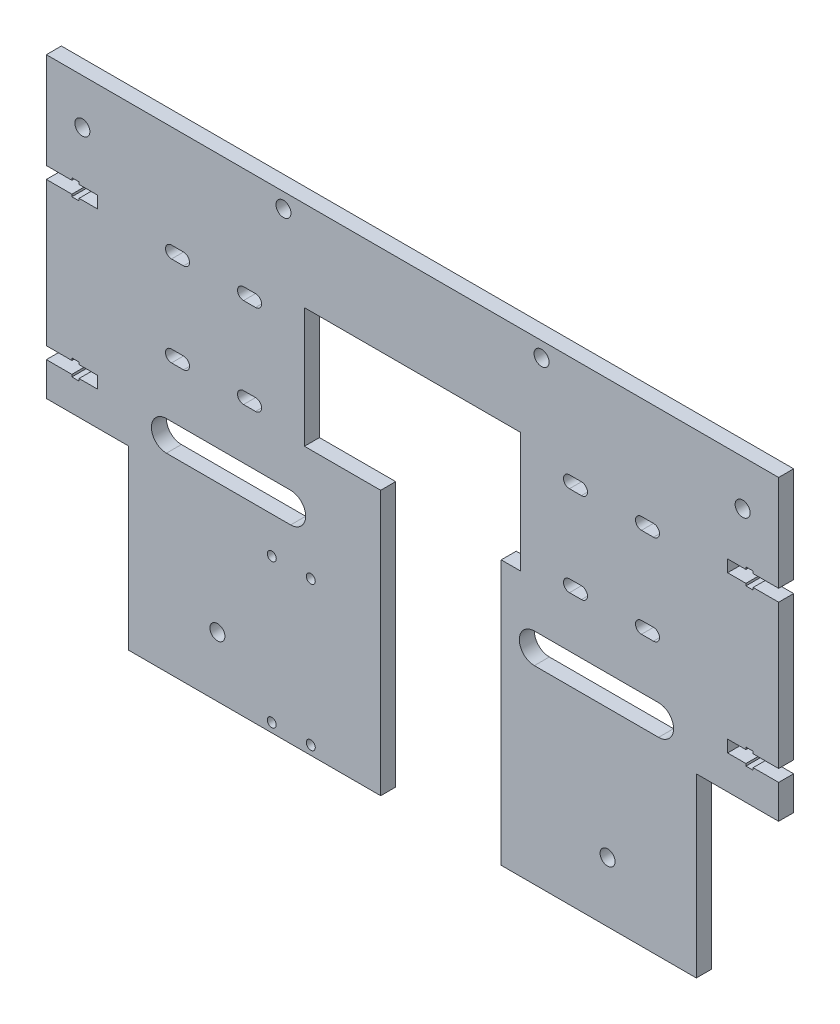
SolidWorks part; units mm, degrees
ref_plane "Front Plane" through (0, 0, 0) normal (0, 0, 1) x (1, 0, 0)
ref_plane "Top Plane" through (0, 0, 0) normal (0, 1, 0) x (1, 0, 0)
ref_plane "Right Plane" through (0, 0, 0) normal (1, 0, 0) x (0, 0, -1)
sketch "Sketch1" plane through (0, 0, 0) normal (0, 0, 1) x (1, 0, 0)
  line L12 (-36.308, -115.936) -> (-36.308, 42.2186)
  line L16 (-36.308, -115.936) -> (-280.308, -115.936)
  line L18 (-280.308, -115.936) -> (-280.308, 42.2186)
  line L20 (-280.308, 42.2186) -> (-36.308, 42.2186)
  dimension "D1" = 244
  dimension "D2" = 158.1546
extrude "Boss-Extrude1" add sketch "Sketch1" along normal blind 5
sketch "Sketch7" plane through (0, 0, 0) normal (0, 0, -1) x (-1, 0, 0)
  line L6 (280.308, -57.0152) -> (252.8877, -57.0152)
  line L7 (252.8877, -57.0152) -> (252.8877, -115.936)
  line L8 (280.308, -115.936) -> (36.308, -115.936) construction
  line L10 (280.308, -115.936) -> (280.308, -57.0152)
  line L11 (280.308, -115.936) -> (252.8877, -115.936)
  line L12 (158.308, -115.936) -> (158.308, 20.5632) construction
  line L13 (36.308, -115.936) -> (63.7283, -115.936)
  line L14 (63.7283, -57.0152) -> (63.7283, -115.936)
  line L15 (36.308, -57.0152) -> (63.7283, -57.0152)
  line L16 (36.308, -115.936) -> (36.308, -57.0152)
  line L19 (280.308, 42.2186) -> (280.308, -115.936) construction
  line L22 (36.308, 42.2186) -> (280.308, 42.2186) construction
  line L24 (122.308, 12.2186) -> (122.308, -27.7814)
  line L26 (194.308, 12.2186) -> (194.308, -27.7814)
  line L27 (122.308, 12.2186) -> (194.308, 12.2186)
  line L28 (122.308, -27.7814) -> (194.308, -27.7814)
  line L30 (33.308, 42.2186) -> (33.308, 26.2186) construction
  dimension "D1" = 40
  dimension "D2" = 72
  dimension "D3" = 89
  dimension "D4" = 27.4203
  dimension "D5" = 58.9208
  dimension "D6" = 30
extrude "Cut-Extrude3" cut sketch "Sketch7" against normal blind 10
ref_plane "Plane1" through (-280.308, -57.0152, 5) normal (0, -1, 0) x (-1, 0, 0)
sketch "Sketch8" plane through (0, 0, 5) normal (0, 0, 1) x (1, 0, 0)
  line L0 (-252.8877, -115.936) -> (-63.7283, -115.936) construction
  line L1 (-128.7488, -115.936) -> (-168.908, -115.936)
  line L2 (-128.7488, -115.936) -> (-128.7488, -27.7814)
  line L3 (-128.7488, -27.7814) -> (-168.908, -27.7814)
  line L4 (-168.908, -115.936) -> (-168.908, -27.7814)
  line L5 (-122.308, -27.7814) -> (-194.308, -27.7814) construction
extrude "Cut-Extrude4" cut sketch "Sketch8" against normal blind 10
sketch "Sketch9" plane through (0, 0, 5) normal (0, 0, 1) x (1, 0, 0)
  line L0 (-280.308, 42.2186) -> (-280.308, -57.0152) construction
  line L1 (-36.308, 42.2186) -> (-280.308, 42.2186) construction
  line L2 (-252.8877, -57.0152) -> (-252.8877, -115.936) construction
  line L3 (-252.8877, -115.936) -> (-168.908, -115.936) construction
  line L4 (-63.7283, -115.936) -> (-63.7283, -57.0152) construction
  circle A0 centre (-93.308, -95.936) radius 2.5
  circle A1 centre (-223.308, -95.936) radius 2.5
  circle A2 centre (-268.308, 27.2186) radius 2.5
  circle A3 centre (-48.308, 27.2186) radius 2.5
  circle A4 centre (-115.308, 37.2186) radius 2.5
  circle A5 centre (-201.308, 37.2186) radius 2.5
  dimension "D1" = 5
  dimension "D2" = 5
  dimension "D3" = 5
  dimension "D4" = 5
  dimension "D5" = 5
  dimension "D6" = 5
  dimension "D7" = 12
  dimension "D8" = 15
  dimension "D9" = 220
  dimension "D10" = 86
  dimension "D11" = 5
  dimension "D12" = 79
  dimension "D13" = 29.5797
  dimension "D14" = 20
  dimension "D15" = 29.5797
extrude "Cut-Extrude5" cut sketch "Sketch9" against normal blind 10
sketch "Sketch10" plane through (0, 0, 5) normal (0, 0, 1) x (1, 0, 0)
  line L0 (-280.308, 42.2186) -> (-280.308, -57.0152) construction
  line L1 (-280.308, 10.2186) -> (-271.808, 10.2186)
  line L2 (-280.308, 10.2186) -> (-280.308, 6.2186)
  line L3 (-280.308, 6.2186) -> (-271.808, 6.2186)
  line L4 (-263.308, 10.2186) -> (-263.308, 6.2186)
  line L5 (-36.308, 42.2186) -> (-280.308, 42.2186) construction
  line L10 (-271.808, 10.2186) -> (-271.808, 10.9686)
  line L12 (-269.408, 10.9686) -> (-269.408, 10.2186)
  line L13 (-269.408, 6.8436) -> (-269.408, 9.5936) construction
  line L15 (-271.808, 6.2186) -> (-271.808, 5.4664)
  line L17 (-269.408, 5.4664) -> (-269.408, 6.2186)
  line L18 (-269.408, 5.4686) -> (-269.408, 6.8436) construction
  line L19 (-300.6549, -17.7814) -> (-246.3627, -17.7814) construction
  line L20 (-269.408, 10.2186) -> (-263.308, 10.2186)
  line L21 (-269.408, 6.2186) -> (-263.308, 6.2186)
  line L29 (-271.808, -41.7814) -> (-271.808, -41.0292)
  line L30 (-158.308, 42.2186) -> (-158.308, -122.1945) construction
  line L31 (-269.408, -41.0292) -> (-271.808, -41.0292)
  line L32 (-269.408, -41.0292) -> (-269.408, -41.7814)
  line L33 (-269.408, -41.7814) -> (-263.308, -41.7814)
  line L34 (-263.308, -45.7814) -> (-263.308, -41.7814)
  line L35 (-269.408, -45.7814) -> (-263.308, -45.7814)
  line L36 (-269.408, -46.5314) -> (-269.408, -45.7814)
  line L37 (-271.808, -45.7814) -> (-271.808, -46.5314)
  line L38 (-271.808, -46.5314) -> (-269.408, -46.5314)
  line L44 (-280.308, -41.7814) -> (-271.808, -41.7814)
  line L48 (-280.308, -45.7814) -> (-280.308, -41.7814)
  line L49 (-280.308, -45.7814) -> (-271.808, -45.7814)
  line L50 (-53.308, -45.7814) -> (-53.308, -41.7814)
  line L51 (-47.208, -45.7814) -> (-53.308, -45.7814)
  line L56 (-271.808, 10.9686) -> (-269.408, 10.9686)
  line L57 (-269.408, 5.4664) -> (-271.808, 5.4664)
  line L58 (-47.208, -46.5314) -> (-47.208, -45.7814)
  line L59 (-44.808, -45.7814) -> (-44.808, -46.5314)
  line L60 (-44.808, -46.5314) -> (-47.208, -46.5314)
  line L61 (-36.308, -45.7814) -> (-36.308, -41.7814)
  line L62 (-36.308, -45.7814) -> (-44.808, -45.7814)
  line L63 (-44.808, -41.7814) -> (-44.808, -41.0292)
  line L64 (-47.208, -41.0292) -> (-44.808, -41.0292)
  line L65 (-47.208, -41.0292) -> (-47.208, -41.7814)
  line L66 (-47.208, -41.7814) -> (-53.308, -41.7814)
  line L67 (-36.308, -41.7814) -> (-44.808, -41.7814)
  line L68 (-36.308, 10.2186) -> (-36.308, 6.2186)
  line L69 (-36.308, 10.2186) -> (-44.808, 10.2186)
  line L70 (-36.308, 6.2186) -> (-44.808, 6.2186)
  line L71 (-44.808, 6.2186) -> (-44.808, 5.4664)
  line L72 (-47.208, 5.4664) -> (-47.208, 6.2186)
  line L73 (-47.208, 5.4664) -> (-44.808, 5.4664)
  line L74 (-53.308, 10.2186) -> (-53.308, 6.2186)
  line L75 (-47.208, 6.2186) -> (-53.308, 6.2186)
  line L76 (-47.208, 10.9686) -> (-47.208, 10.2186)
  line L77 (-44.808, 10.2186) -> (-44.808, 10.9686)
  line L78 (-44.808, 10.9686) -> (-47.208, 10.9686)
  line L79 (-47.208, 10.2186) -> (-53.308, 10.2186)
  line L80 (-280.308, 8.2186) -> (-260.8757, 8.2186) construction
  line L81 (-280.308, -43.7814) -> (-257.6752, -43.7814) construction
  point P29 (-270.608, -40.6298)
  point P62 (-46.008, -40.6298)
  line M26 (-36.308, -57.0152) -> (-36.308, 42.2186)
  line M28 (-280.308, 42.2186) -> (-280.308, -57.0152)
  dimension "D1" = 4
  dimension "D2" = 17
  dimension "D3" = 0.75
  dimension "D4" = 0.7522
  dimension "D5" = 2.4
  dimension "D6" = 32
extrude "Cut-Extrude6" cut sketch "Sketch10" against normal blind 10 contours L57 L17 L21 L4 L20 L12 L56 L10 L1 L3 L15 M28 | L49 L37 L38 L36 L35 L34 L33 L32 L31 L29 L44 M28 | L67 L63 L64 L65 L66 L50 L51 L58 L60 L59 L62 M26 | L76 L79 L74 L75 L72 L73 L71 L70 L69 L77 L78 M26
sketch "Sketch13" plane through (0, 0, 5) normal (0, 0, 1) x (1, 0, 0)
  line L0 (-168.908, -27.7814) -> (-168.908, -115.936) construction
  line L1 (-252.8877, -115.936) -> (-168.908, -115.936) construction
  circle A1 centre (-205.2054, -112.936) radius 1.5
  circle A3 centre (-205.2054, -64.936) radius 1.5
  circle A5 centre (-192.2054, -112.936) radius 1.5
  circle A7 centre (-192.2054, -64.936) radius 1.5
  dimension "D2" = 3
  dimension "D3" = 3
  dimension "D4" = 3
  dimension "D5" = 3
  dimension "D1" = 48
  dimension "D6" = 13
  dimension "D7" = 23.2974
  dimension "D8" = 51
  dimension "D9" = 48
extrude "Cut-Extrude8" cut sketch "Sketch13" against normal blind 10
sketch "Sketch15" plane through (0, 0, 5) normal (0, 0, 1) x (1, 0, 0)
  line L0 (-198.908, -42.7814) -> (-240.308, -42.7814)
  line L2 (-240.308, -52.7814) -> (-198.908, -52.7814)
  line L4 (-280.308, 6.2186) -> (-280.308, -41.7814) construction
  line L5 (-168.908, -27.7814) -> (-168.908, -115.936) construction
  line L6 (-36.308, 42.2186) -> (-280.308, 42.2186) construction
  line L7 (-158.308, 42.2186) -> (-158.308, -127.6006) construction
  line L8 (-117.708, -42.7814) -> (-76.308, -42.7814)
  line L9 (-76.308, -52.7814) -> (-117.708, -52.7814)
  arc A0 (-240.308, -42.7814) -> (-240.308, -52.7814) centre (-240.308, -47.7814) ccw
  arc A1 (-198.908, -42.7814) -> (-198.908, -52.7814) centre (-198.908, -47.7814) cw
  arc A2 (-117.708, -42.7814) -> (-117.708, -52.7814) centre (-117.708, -47.7814) ccw
  arc A3 (-76.308, -42.7814) -> (-76.308, -52.7814) centre (-76.308, -47.7814) cw
  dimension "D2" = 40
  dimension "D1" = 10
  dimension "D3" = 30
  dimension "D4" = 90
extrude "Cut-Extrude10" cut sketch "Sketch15" against normal blind 10
sketch "Sketch16" plane through (0, 0, 5) normal (0, 0, 1) x (1, 0, 0)
  line L0 (-212.608, -25.8814) -> (-210.608, -25.8814)
  line L2 (-210.608, -21.8814) -> (-214.608, -21.8814)
  line L4 (-214.608, -25.8814) -> (-212.608, -25.8814)
  line L5 (-236.608, -25.8814) -> (-234.608, -25.8814)
  line L7 (-234.608, -21.8814) -> (-238.608, -21.8814)
  line L9 (-238.608, -25.8814) -> (-236.608, -25.8814)
  line L10 (-212.608, 4.1186) -> (-210.608, 4.1186)
  line L11 (-212.608, 8.1186) -> (-210.608, 8.1186)
  line L13 (-212.608, 4.1186) -> (-214.608, 4.1186)
  line L15 (-214.608, 8.1186) -> (-212.608, 8.1186)
  line L16 (-236.608, 4.1186) -> (-234.608, 4.1186)
  line L18 (-234.608, 8.1186) -> (-238.608, 8.1186)
  line L20 (-238.608, 4.1186) -> (-236.608, 4.1186)
  line L21 (-158.308, 42.2186) -> (-158.308, -115.178) construction
  line L22 (-36.308, 42.2186) -> (-280.308, 42.2186) construction
  line L23 (-78.008, 4.1186) -> (-80.008, 4.1186)
  line L24 (-82.008, 8.1186) -> (-78.008, 8.1186)
  line L25 (-80.008, 4.1186) -> (-82.008, 4.1186)
  line L26 (-78.008, -25.8814) -> (-80.008, -25.8814)
  line L27 (-82.008, -21.8814) -> (-78.008, -21.8814)
  line L28 (-80.008, -25.8814) -> (-82.008, -25.8814)
  line L29 (-102.008, 8.1186) -> (-104.008, 8.1186)
  line L30 (-104.008, 4.1186) -> (-102.008, 4.1186)
  line L31 (-104.008, 8.1186) -> (-106.008, 8.1186)
  line L32 (-104.008, 4.1186) -> (-106.008, 4.1186)
  line L33 (-102.008, -25.8814) -> (-104.008, -25.8814)
  line L34 (-106.008, -21.8814) -> (-102.008, -21.8814)
  line L35 (-104.008, -25.8814) -> (-106.008, -25.8814)
  arc A8 (-210.608, -25.8814) -> (-210.608, -21.8814) centre (-210.608, -23.8814) ccw
  arc A9 (-214.608, -21.8814) -> (-214.608, -25.8814) centre (-214.608, -23.8814) ccw
  arc A10 (-210.608, 4.1186) -> (-210.608, 8.1186) centre (-210.608, 6.1186) ccw
  arc A11 (-214.608, 4.1186) -> (-214.608, 8.1186) centre (-214.608, 6.1186) cw
  arc A12 (-234.608, -25.8814) -> (-234.608, -21.8814) centre (-234.608, -23.8814) ccw
  arc A13 (-238.608, -21.8814) -> (-238.608, -25.8814) centre (-238.608, -23.8814) ccw
  arc A14 (-234.608, 4.1186) -> (-234.608, 8.1186) centre (-234.608, 6.1186) ccw
  arc A15 (-238.608, 4.1186) -> (-238.608, 8.1186) centre (-238.608, 6.1186) cw
  arc A16 (-78.008, 4.1186) -> (-78.008, 8.1186) centre (-78.008, 6.1186) ccw
  arc A17 (-82.008, 4.1186) -> (-82.008, 8.1186) centre (-82.008, 6.1186) cw
  arc A18 (-78.008, -21.8814) -> (-78.008, -25.8814) centre (-78.008, -23.8814) cw
  arc A19 (-82.008, -25.8814) -> (-82.008, -21.8814) centre (-82.008, -23.8814) cw
  arc A20 (-102.008, 4.1186) -> (-102.008, 8.1186) centre (-102.008, 6.1186) ccw
  arc A21 (-106.008, 4.1186) -> (-106.008, 8.1186) centre (-106.008, 6.1186) cw
  arc A22 (-102.008, -21.8814) -> (-102.008, -25.8814) centre (-102.008, -23.8814) cw
  arc A23 (-106.008, -25.8814) -> (-106.008, -21.8814) centre (-106.008, -23.8814) cw
extrude "Cut-Extrude11" cut sketch "Sketch16" against normal blind 10
